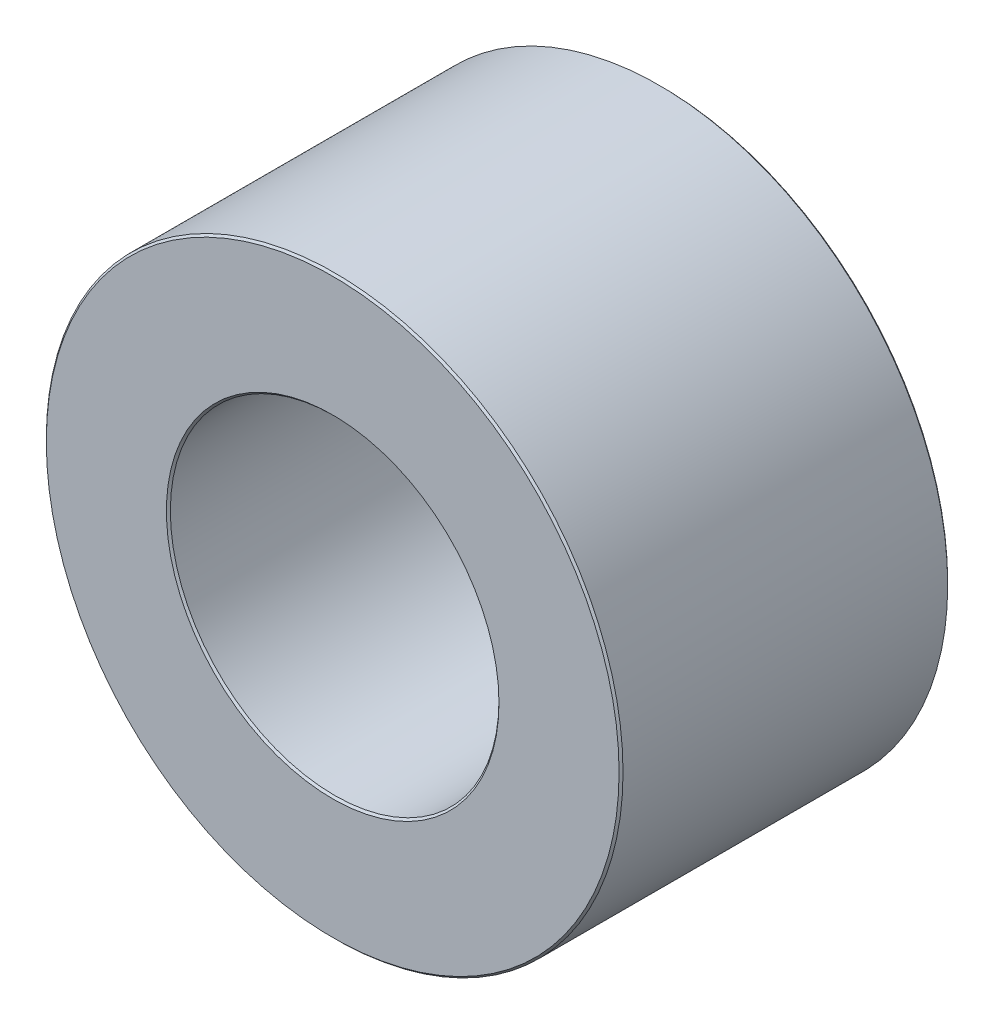
SolidWorks part; units mm, degrees
ref_plane "Front Plane" through (0, 0, 0) normal (0, 0, 1) x (1, 0, 0)
ref_plane "Top Plane" through (0, 0, 0) normal (0, 1, 0) x (1, 0, 0)
ref_plane "Right Plane" through (0, 0, 0) normal (1, 0, 0) x (0, 0, -1)
sketch "Sketch1" plane through (0, 0, 0) normal (0, 0, 1) x (1, 0, 0)
  circle A0 centre (0, 0) radius 3.51
  circle A1 centre (0, 0) radius 2
  point P8 (0, -3.51)
  point P9 (0, 3.51)
  dimension "ID" = 4
  dimension "OD" = 7.02
sketch "Sketch2" plane through (0, 0, 0) normal (1, 0, 0) x (0, 0, -1)
  line L0 (2, 0) -> (-2, 0) construction
  line L1 (2, 3.51) -> (-2, 3.51) construction
  point P4 (0, 0)
  point P8 (0, 3.51)
  point P9 (0, 3.51)
  dimension "Length" = 4
sketch "Sketch5" plane through (0, 0, 0) normal (0, 0, 1) x (1, 0, 0)
  circle A0 centre (0, 0) radius 2 construction
  circle A1 centre (0, 0) radius 3.51 construction
  circle A2 centre (0, 0) radius 2
  circle A3 centre (0, 0) radius 3.51
extrude "Boss-Extrude1" add sketch "Sketch5" along normal up to vertex (2 mm away) and the other way up to vertex (2 mm away) up to point (0, 0, 2) other way up to point (0, 0, -2)
chamfer "Chamfer1" distance 0.024 angle 45 4 edges at (3.51, 0, -2) (2, 0, -2) (2, 0, 2) (3.51, 0, 2)
equation "\"D1@Chamfer1\"=\"ID@Sketch1\"*.006"
